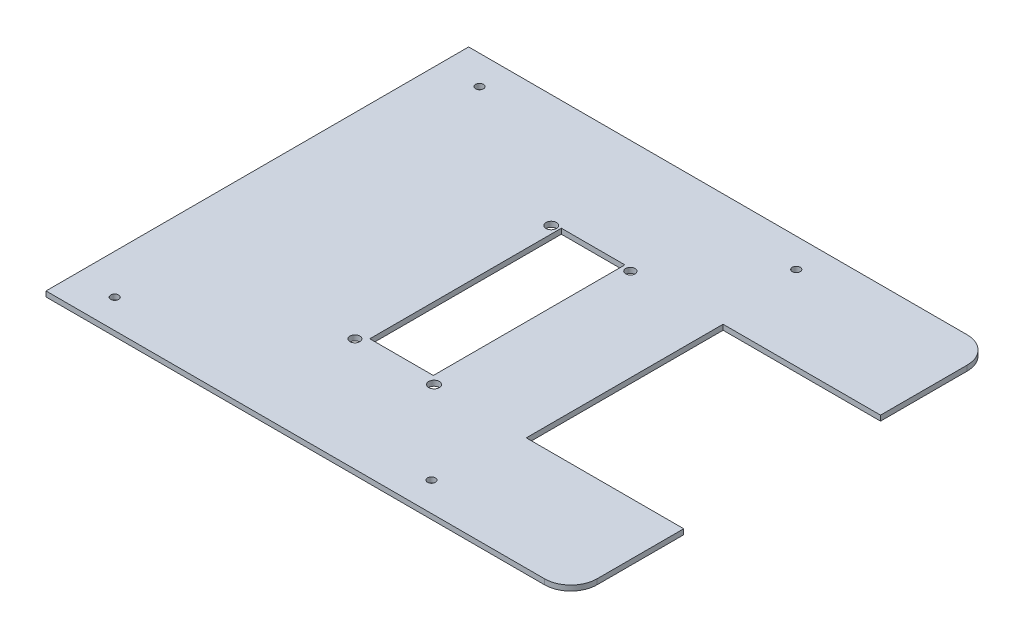
SolidWorks part; units mm, degrees
ref_plane "Front Plane" through (0, 0, 0) normal (0, 0, 1) x (1, 0, 0)
ref_plane "Top Plane" through (0, 0, 0) normal (0, 1, 0) x (1, 0, 0)
ref_plane "Right Plane" through (0, 0, 0) normal (1, 0, 0) x (0, 0, -1)
sketch "Sketch1" plane through (0, 0, 0) normal (0, 1, 0) x (1, 0, 0)
  line L0 (62.5, -37.5) -> (62.5, -80.53)
  line L1 (-137.5, 80.53) -> (62.5, 80.53)
  line L2 (-137.5, 80.53) -> (-137.5, -80.53)
  line L3 (-137.5, -80.53) -> (62.5, -80.53)
  line L4 (62.5, 80.53) -> (62.5, 37.5)
  line L5 (0, 0) -> (2.5, -3) construction
  line L6 (0, 0) -> (2.5, 3) construction
  line L7 (2.5, 37.5) -> (62.5, 37.5)
  line L8 (2.5, 37.5) -> (2.5, -37.5)
  line L9 (2.5, -37.5) -> (62.5, -37.5)
  point P0 (0, 0)
  point P5 (32.5, 0)
  dimension "D1" = 161.06
  dimension "D2" = 200
  dimension "D3" = 75
  dimension "D4" = 60
  dimension "D5" = 0
  dimension "D6" = 32.5
  dimension "D7" = 80.53
  dimension "D8" = 37.5
extrude "Boss-Extrude1" add sketch "Sketch1" along normal blind 2
sketch "Sketch2" plane through (0, 2, 0) normal (0, 1, 0) x (1, 0, 0)
  line L0 (26.8587, 0) -> (-74.6271, 0) construction
  line L1 (-33.8873, 69.5158) -> (-33.8873, -74.7684) construction
  line L8 (-47.8873, 65.7902) -> (-47.8873, -63.5177) construction
  line L9 (-137.5, 80.53) -> (-137.5, -80.53) construction
  line L10 (2.5, -37.5) -> (2.5, 37.5) construction
  line L11 (-7.5095, 1.8781) -> (-83.7359, 1.8781) construction
  line L12 (-60.0097, -34.6246) -> (-35.7971, -34.6246)
  line L13 (-60.0097, -34.6246) -> (-60.0097, 38.3754)
  line L14 (-60.0097, 38.3754) -> (-35.7971, 38.3754)
  line L15 (-35.7971, -34.6246) -> (-35.7971, 38.3754)
  line L16 (-60.0097, -34.6246) -> (-35.7971, 38.3754) construction
  line L17 (-60.0097, 38.3754) -> (-35.7971, -34.6246) construction
  circle A0 centre (-122.3325, -69.5158) radius 1.5
  circle A1 centre (-1.6235, -69.5158) radius 1.5
  circle A2 centre (-122.3325, 69.5158) radius 1.5
  circle A3 centre (-1.6235, 69.5158) radius 1.5
  circle A8 centre (-32.6708, 37.3318) radius 1.7928
  circle A9 centre (-62.8258, 37.3318) radius 1.9942
  circle A10 centre (-62.8258, -37.4777) radius 1.8774
  circle A11 centre (-32.6708, -37.4777) radius 2.0309
  point P23 (-33.7502, -0.0765)
  point P24 (-33.8472, 1.8781)
  point P47 (-47.8065, -0.0792)
  point P48 (-47.9034, 1.8754)
  dimension "D3" = 14
  dimension "D4" = 36.3873
  dimension "D5" = 73
  dimension "D6" = 24.2125
extrude "Cut-Extrude1" cut sketch "Sketch2" against normal up to surface (2 mm away) up to face at (-2.5, 0, 0)
fillet "Fillet1" radius 10 2 edges at (62.5, 1, -80.53) (62.5, 1, 80.53)
